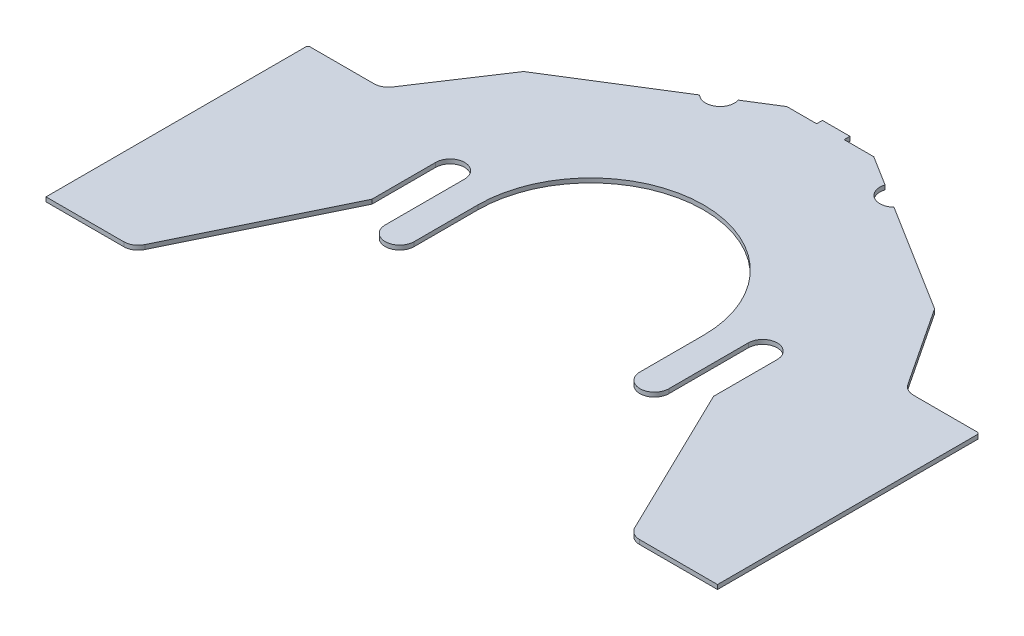
SolidWorks part; units mm, degrees
ref_plane "Front Plane" through (0, 0, 0) normal (0, 0, 1) x (1, 0, 0)
ref_plane "Top Plane" through (0, 0, 0) normal (0, 1, 0) x (1, 0, 0)
ref_plane "Right Plane" through (0, 0, 0) normal (1, 0, 0) x (0, 0, -1)
sketch "Sketch1" plane through (0, 0, 0) normal (0, 1, 0) x (1, 0, 0)
  line L0 (15, 0) -> (4.75, 0)
  line L1 (-15, 0) -> (-25.3566, -6.4729)
  line L2 (-33.5751, -11.6094) -> (-71, -35)
  line L3 (-71, -35) -> (-89.0174, -62.2572)
  line L4 (-93.1885, -64.5) -> (-115.5, -64.5)
  line L5 (-115.5, -64.5) -> (-116, -65)
  line L6 (-116, -65) -> (-116, -155)
  line L7 (-116, -155) -> (-89.1311, -155)
  line L8 (-84.6329, -152.1832) -> (-59, -99.3692)
  line L9 (-59, -99.3692) -> (-59, -77.3692)
  line L10 (0, 0) -> (0, 21.0203) construction
  line L11 (-49, -77.3692) -> (-49, -104.8009)
  line L12 (39, -104.8009) -> (39, -82.8009)
  line L13 (-39, -104.8009) -> (-39, -82.8009)
  line L14 (49, -77.3692) -> (49, -104.8009)
  line L15 (59, -99.3692) -> (59, -77.3692)
  line L16 (84.6329, -152.1832) -> (59, -99.3692)
  line L17 (116, -155) -> (89.1311, -155)
  line L18 (116, -65) -> (116, -155)
  line L19 (115.5, -64.5) -> (116, -65)
  line L20 (93.1885, -64.5) -> (115.5, -64.5)
  line L21 (71, -35) -> (89.0174, -62.2572)
  line L22 (33.5751, -11.6094) -> (71, -35)
  line L23 (15, 0) -> (25.3566, -6.4729)
  line L24 (-4.75, 0) -> (-15, 0)
  line L26 (-4.75, 0) -> (-4.75, 2)
  line L27 (-4.75, 2) -> (4.75, 2)
  line L28 (4.75, 0) -> (4.75, 2)
  line L29 (-4.75, -2) -> (4.75, 2) construction
  line L30 (-4.75, 2) -> (4.75, -2) construction
  arc A0 (-25.3566, -6.4729) -> (-33.5751, -11.6094) centre (-30.1188, -7.9963) cw
  arc A1 (-59, -77.3692) -> (-49, -77.3692) centre (-54, -77.3692) cw
  arc A2 (-49, -104.8009) -> (-39, -104.8009) centre (-44, -104.8009) ccw
  arc A3 (49, -104.8009) -> (39, -104.8009) centre (44, -104.8009) cw
  arc A4 (59, -77.3692) -> (49, -77.3692) centre (54, -77.3692) ccw
  arc A5 (25.3566, -6.4729) -> (33.5751, -11.6094) centre (30.1188, -7.9963) ccw
  arc A6 (-39, -82.8009) -> (39, -82.8009) centre (0, -82.8009) cw
  arc A7 (-84.6329, -152.1832) -> (-89.1311, -155) centre (-89.1311, -150) cw
  arc A8 (-89.0174, -62.2572) -> (-93.1885, -64.5) centre (-93.1885, -59.5) cw
  arc A9 (89.1311, -155) -> (84.6329, -152.1832) centre (89.1311, -150) cw
  arc A10 (93.1885, -64.5) -> (89.0174, -62.2572) centre (93.1885, -59.5) cw
  point P20 (-54, -72.3692)
  point P21 (-44, -109.8009)
  point P50 (-86, -155)
  point P53 (-90.5, -64.5)
  point P56 (86, -155)
  point P59 (90.5, -64.5)
  dimension "D11" = 5
  dimension "D17" = 39
  dimension "D20" = 5
  dimension "D21" = 5
  dimension "D1" = 155
  dimension "D2" = 90
  dimension "D3" = 0.5
  dimension "D4" = 135
  dimension "D5" = 25
  dimension "D6" = 45
  dimension "D7" = 120
  dimension "D8" = 15
  dimension "D9" = 57
  dimension "D10" = 10
  dimension "D12" = 30
  dimension "D13" = 232
  dimension "D14" = 10
  dimension "D15" = 27
  dimension "D16" = 27
  dimension "D18" = 9.5
  dimension "D19" = 4
extrude "Boss-Extrude1" add sketch "Sketch1" along normal blind 1.5
